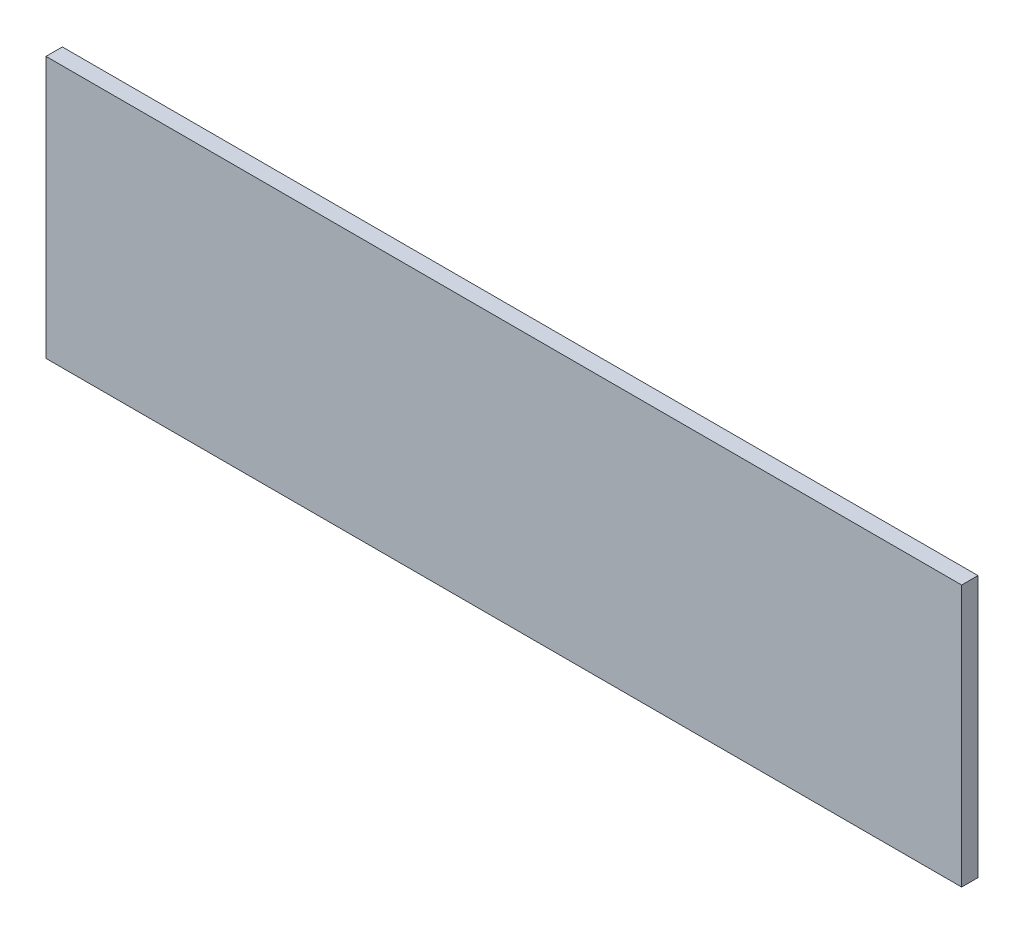
SolidWorks part; units mm, degrees
material "Glass"
ref_plane "Front Plane" through (0, 0, 0) normal (0, 0, 1) x (1, 0, 0)
ref_plane "Top Plane" through (0, 0, 0) normal (0, 1, 0) x (1, 0, 0)
ref_plane "Right Plane" through (0, 0, 0) normal (1, 0, 0) x (0, 0, -1)
sketch "Sketch1" plane through (0, 0, 0) normal (0, 0, 1) x (1, 0, 0)
  line L1 (0, 0) -> (177.8, 0)
  line L2 (0, 0) -> (0, 50.8)
  line L3 (0, 50.8) -> (177.8, 50.8)
  line L4 (177.8, 0) -> (177.8, 50.8)
  dimension "D1" = 177.8
  dimension "D2" = 50.8
extrude "Boss-Extrude1" add sketch "Sketch1" along normal blind 3.175
